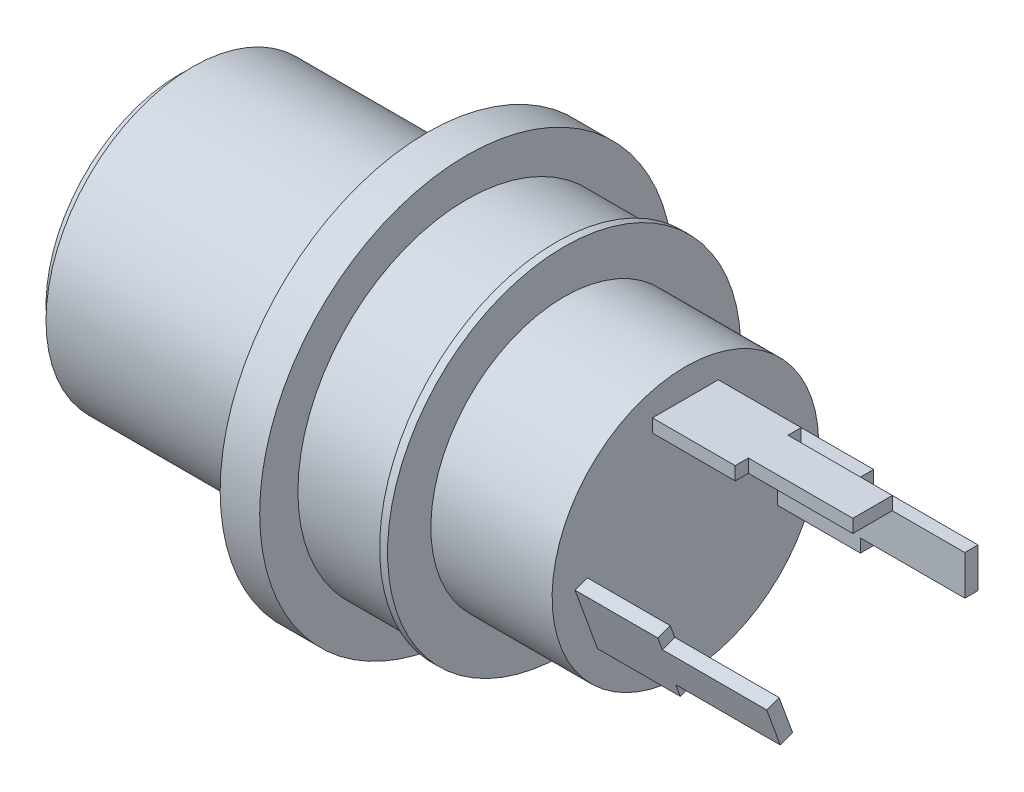
SolidWorks part; units mm, degrees
material "Nickel silver 65-12, UNS C75700"
ref_plane "Front Plane" through (0, 0, 0) normal (0, 0, 1) x (1, 0, 0)
ref_plane "Top Plane" through (0, 0, 0) normal (0, 1, 0) x (1, 0, 0)
ref_plane "Right Plane" through (0, 0, 0) normal (1, 0, 0) x (0, 0, -1)
sketch "Sketch1" plane through (0, 0, 0) normal (0, 0, 1) x (1, 0, 0)
  line L0 (0, 0) -> (-19.2, 0) construction
  line L1 (-19.2, 0) -> (-19.2, 5.0562)
  line L2 (-19.2, 5.0562) -> (-18.7, 5.0562)
  line L3 (-18.7, 5.0562) -> (-18.7, 5.5562)
  line L4 (-18.7, 5.5562) -> (-9.8, 5.5562)
  line L5 (-9.8, 5.5562) -> (-9.8, 7.85)
  line L6 (-9.8, 7.85) -> (-8.3, 7.85)
  line L7 (-8.3, 7.85) -> (-8.3, 6.4)
  line L8 (-8.3, 6.4) -> (-4.9, 6.4)
  line L9 (-4.9, 6.4) -> (-4.9, 6.7)
  line L10 (-4.9, 6.7) -> (-4.6, 6.7)
  line L11 (-4.6, 6.7) -> (-4.6, 5.0562)
  line L12 (-4.6, 5.0562) -> (0, 5.0562)
  line L13 (0, 5.0562) -> (0, 0)
  line L14 (0, 0) -> (-19.2, 0)
  point P15 (0, 0)
  point P16 (0, 0)
  dimension "D1" = 11.1125
  dimension "D2" = 9.4
  dimension "D3" = 15.7
  dimension "D4" = 13.4
  dimension "D5" = 0.3
  dimension "D6" = 19.2
  dimension "D7" = 0.5
  dimension "D8" = 1.5
  dimension "D9" = 5.2
revolve "Revolve1" add sketch "Sketch1" angle 360 about L0
sketch "Sketch2" plane through (-19.2, 0, 0) normal (-1, 0, 0) x (0, 0, 1)
  circle A0 centre (0, 0) radius 3.5563
  circle A1 centre (0, 0) radius 5.0563 construction
  dimension "D1" = 1.5
extrude "Cut-Extrude1" cut sketch "Sketch2" against normal offset from surface (7.9 mm away) 1.5 up to face at (-9.8, 5.5562, 0)
sketch "Sketch3" plane through (0, 0, 0) normal (1, 0, 0) x (0, 0, -1)
  line L0 (-1.25, 3.75) -> (1.25, 3.75)
  line L1 (3.75, 1.25) -> (3.75, -1.25)
  line L2 (-3.9514, -0.108) -> (-3.0963, -2.4572)
  line L3 (0, 3.75) -> (0, 0) construction
  line L4 (0, 0) -> (3.75, 0) construction
  line L5 (0, 0) -> (-3.5238, -1.2826) construction
  dimension "D1" = 2.5
  dimension "D2" = 20
  dimension "D3" = 3.75
extrude "Extrude-Thin1" add sketch "Sketch3" along normal offset from surface (7.1 mm away) 26.3 thin up to face at (-19.2, -3.5563, 0) thin type mid plane wall 0.5
sketch "Sketch4" plane through (7.1, 0, 0) normal (1, 0, 0) x (0, 0, -1)
  line L0 (1.25, 3.5) -> (-1.25, 3.5) construction
  line L1 (-1.25, 4) -> (-0.75, 4)
  line L2 (-1.25, 4) -> (-1.25, 3.5)
  line L3 (-1.25, 3.5) -> (-0.75, 3.5)
  line L4 (-0.75, 4) -> (-0.75, 3.5)
  line L5 (1.25, 4) -> (-1.25, 4) construction
  line L6 (1.25, 3.5) -> (0.75, 3.5)
  line L7 (1.25, 3.5) -> (1.25, 4)
  line L8 (1.25, 4) -> (0.75, 4)
  line L9 (0.75, 3.5) -> (0.75, 4)
  line L10 (4, 1.25) -> (4, -1.25) construction
  line L11 (3.5, 1.25) -> (4, 1.25)
  line L12 (3.5, 1.25) -> (3.5, 0.75)
  line L13 (3.5, 0.75) -> (4, 0.75)
  line L14 (4, 1.25) -> (4, 0.75)
  line L15 (4, -1.25) -> (4, 1.25) construction
  line L16 (3.5, -1.25) -> (4, -1.25)
  line L17 (3.5, -1.25) -> (3.5, -0.75)
  line L18 (3.5, -0.75) -> (4, -0.75)
  line L19 (4, -1.25) -> (4, -0.75)
  line L20 (-3.3312, -2.5427) -> (-2.8614, -2.3717)
  line L21 (-3.3312, -2.5427) -> (-3.5023, -2.0729)
  line L22 (-2.8614, -2.3717) -> (-3.0324, -1.9018)
  line L23 (-3.5023, -2.0729) -> (-3.0324, -1.9018)
  line L24 (-3.7164, -0.0225) -> (-4.1863, -0.1935)
  line L25 (-3.7164, -0.0225) -> (-3.5454, -0.4923)
  line L26 (-4.1863, -0.1935) -> (-4.0153, -0.6633)
  line L27 (-3.5454, -0.4923) -> (-4.0153, -0.6633)
extrude "Cut-Extrude3" cut sketch "Sketch4" against normal blind 3.96
